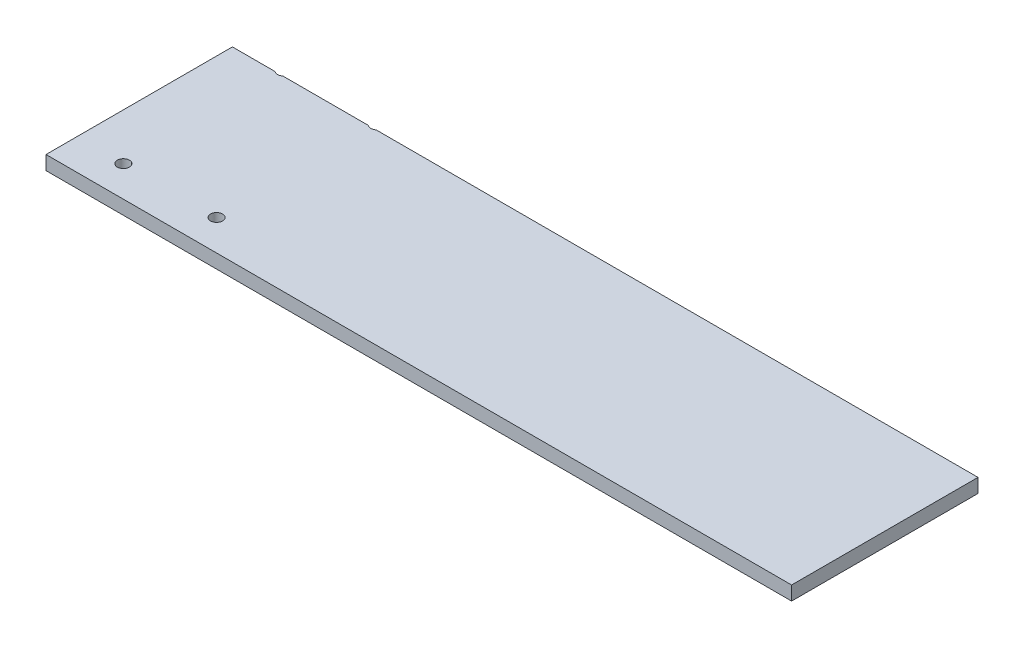
SolidWorks part; units mm, degrees
material "Plain Carbon Steel"
ref_plane "Front Plane" through (0, 0, 0) normal (0, 0, 1) x (1, 0, 0)
ref_plane "Top Plane" through (0, 0, 0) normal (0, 1, 0) x (1, 0, 0)
ref_plane "Right Plane" through (0, 0, 0) normal (1, 0, 0) x (0, 0, -1)
sketch "Sketch1" plane through (0, 0, 0) normal (0, 1, 0) x (1, 0, 0)
  line L0 (0, 0) -> (0, 155.1713) construction
  line L1 (-400, -100) -> (400, -100)
  line L2 (-400, -100) -> (-400, 100)
  line L3 (-400, 100) -> (400, 100)
  line L4 (400, -100) -> (400, 100)
  line L5 (-400, -100) -> (400, 100) construction
  line L6 (-400, 100) -> (400, -100) construction
  line L7 (0, 0) -> (-128.9943, 0) construction
  point P0 (0, 0)
  dimension "D1" = 800
  dimension "D2" = 200
extrude "Boss-Extrude1" add sketch "Sketch1" along normal mid plane 15
sketch "Sketch2" plane through (0, 7.5, 0) normal (0, 1, 0) x (1, 0, 0)
  line L0 (-400, 0) -> (-429.7425, 0) construction
  line L1 (-400, 100) -> (-400, -100) construction
  circle A0 centre (-350, -67) radius 6.5 construction
  circle A1 centre (-350, -67) radius 6.5
  circle A4 centre (-250, -67) radius 6.5 construction
  circle A5 centre (-250, -67) radius 6.5
  circle A8 centre (-350, 105) radius 6.5
  circle A9 centre (-350, 105) radius 6.5
  circle A10 centre (-250, 105) radius 6.5
  circle A11 centre (-250, 105) radius 6.5
  dimension "D1" = 0
  dimension "D2" = 0
extrude "Cut-Extrude1" cut sketch "Sketch2" against normal through all
